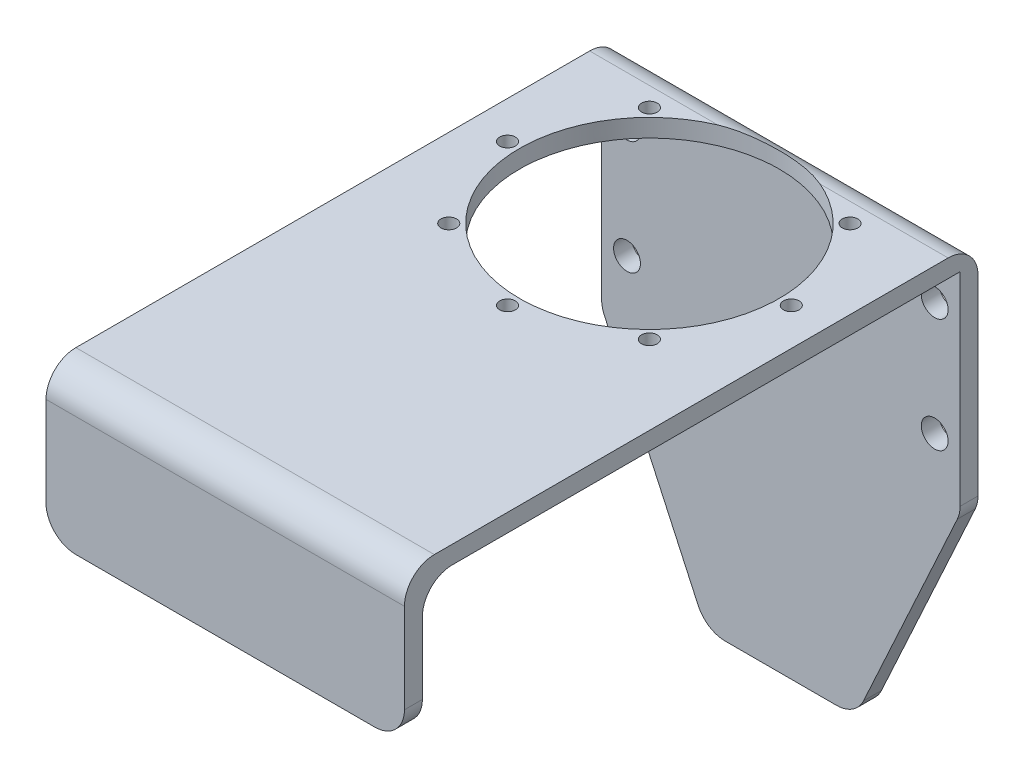
SolidWorks part; units mm, degrees
ref_plane "Alzado" through (0, 0, 0) normal (0, 0, 1) x (1, 0, 0)
ref_plane "Planta" through (0, 0, 0) normal (0, 1, 0) x (1, 0, 0)
ref_plane "Vista lateral" through (0, 0, 0) normal (1, 0, 0) x (0, 0, -1)
sketch "Croquis1" plane through (0, 0, 0) normal (0, 0, 1) x (1, 0, 0)
  line L7 (-92.102, -168.3) -> (-57.102, -244.5)
  line L8 (-92.102, -92.1) -> (27.898, -92.1) construction
  line L9 (-92.102, -92.1) -> (-92.102, -244.5) construction
  line L10 (-92.102, -244.5) -> (27.898, -244.5) construction
  line L11 (27.898, -92.1) -> (27.898, -244.5) construction
  line L12 (27.898, -92.1) -> (27.898, -244.5) construction
  line L13 (-92.102, -92.1) -> (27.898, -92.1) construction
  line L14 (-92.102, -92.1) -> (27.898, -92.1)
  line L15 (-92.102, -92.1) -> (-92.102, -168.3)
  line L17 (27.898, -92.1) -> (27.898, -168.3)
  line L22 (-57.102, -244.5) -> (-7.102, -244.5)
  line L23 (-7.102, -244.5) -> (27.898, -168.3)
  line L24 (-32.102, -168.3) -> (-32.102, -92.1) construction
  line L25 (-92.102, -168.3) -> (27.898, -168.3) construction
  line L26 (-32.102, -130.2) -> (-92.102, -130.2) construction
  line L27 (-62.102, -130.2) -> (-62.102, -92.1) construction
  circle A0 centre (-83.602, -111.15) radius 4.5
  circle A1 centre (-83.602, -149.25) radius 4.5
  circle A2 centre (19.398, -149.25) radius 4.5
  circle A3 centre (19.398, -111.15) radius 4.5
  point P5 (-32.102, -244.5)
  point P16 (-32.102, -244.5)
  point P21 (27.898, -168.3)
  point P24 (-62.102, -111.15)
  point P32 (-88.102, -111.15)
  dimension "D3" = 9
  dimension "D1" = 120
  dimension "D2" = 50
  dimension "D4" = 4
extrude "Saliente-Extruir1" add sketch "Croquis1" along normal blind 6
sketch "Croquis2" plane through (0, 0, 6) normal (0, 0, 1) x (1, 0, 0)
  line L0 (27.898, -168.3) -> (27.898, -92.1) construction
  line L6 (-92.102, -98.1) -> (27.898, -98.1)
  line L7 (-92.102, -98.1) -> (-92.102, -92.1)
  line L8 (-92.102, -92.1) -> (27.898, -92.1)
  line L9 (27.898, -98.1) -> (27.898, -92.1)
  dimension "D1" = 6
extrude "Saliente-Extruir2" add sketch "Croquis2" along normal up to surface (186 mm away)
sketch "Croquis3" plane through (0, 0, 192) normal (0, 0, 1) x (1, 0, 0)
  line L5 (-92.102, -98.1) -> (27.898, -98.1)
  line L6 (-92.102, -98.1) -> (-92.102, -142.1)
  line L7 (-92.102, -142.1) -> (27.898, -142.1)
  line L16 (27.898, -98.1) -> (27.898, -142.1)
  line L17 (27.898, -92.1) -> (-92.102, -92.1) construction
  line L18 (27.898, -168.3) -> (27.898, -98.1) construction
  dimension "50" = 50
extrude "Saliente-Extruir3" add sketch "Croquis3" against normal blind 6
fillet "Redondeo1" radius 10 9 edges at (-32.102, -98.1, 186) (-32.102, -92.1, 0) (-32.102, -92.1, 192) (-92.102, -142.1, 189) (27.898, -142.1, 189) (-92.102, -168.3, 3) (27.898, -168.3, 3) (-7.102, -244.5, 3) (-57.102, -244.5, 3)
sketch "Croquis4" plane through (0, -98.1, 0) normal (0, -1, 0) x (1, 0, 0)
  circle A2 centre (-65.6896, 16.4124) radius 2.621
  circle A3 centre (1.4855, 83.5876) radius 2.621
  circle A4 centre (1.4855, 83.5876) radius 2.621
  circle A5 centre (-65.6896, 16.4124) radius 2.621
  circle A6 centre (15.398, 50) radius 2.621
  circle A7 centre (15.398, 50) radius 2.621
  circle A9 centre (1.4855, 16.4124) radius 2.621
  circle A10 centre (1.4855, 16.4124) radius 2.621
  circle A12 centre (-65.6896, 83.5876) radius 2.621
  circle A13 centre (-65.6896, 83.5876) radius 2.621
  circle A15 centre (-79.602, 50) radius 2.621
  circle A16 centre (-32.102, 97.5) radius 2.621
  circle A17 centre (-32.102, 97.5) radius 2.621
  circle A18 centre (-79.602, 50) radius 2.621
  spline S0 degree 3 poles (-36.0819, 6.6207) (-32.1019, 6.4397) (-28.122, 6.6207) (-24.0966, 7.1778) (-20.0626, 8.1272) (-16.0093, 9.5102) (-12.0574, 11.3088) (-8.2311, 13.545) (-4.6252, 16.1753) (-1.2886, 19.1868) (1.7228, 22.5233) (4.3531, 26.1294) (6.5893, 29.9556) (8.3879, 33.9076) (9.7708, 37.9607) (10.7202, 41.9949) (11.2773, 46.0201) (11.4583, 50.0002) (11.2773, 53.98) (10.7201, 58.0055) (9.7707, 62.0395) (8.3878, 66.0927) (6.5892, 70.0446) (4.353, 73.8709) (1.7226, 77.4768) (-1.2888, 80.8135) (-4.6253, 83.8248) (-8.2314, 86.4552) (-12.0576, 88.6913) (-16.0096, 90.4899) (-20.0627, 91.8728) (-24.0969, 92.8222) (-28.1222, 93.3793) (-32.1022, 93.5603) (-36.0821, 93.3793) (-40.1075, 92.8222) (-44.1415, 91.8727) (-48.1948, 90.4898) (-52.1466, 88.6912) (-55.973, 86.455) (-59.5789, 83.8247) (-62.9155, 80.8132) (-65.9268, 77.4767) (-68.5572, 73.8706) (-70.7934, 70.0444) (-72.592, 66.0924) (-73.9748, 62.0393) (-74.9243, 58.0051) (-75.4813, 53.9799) (-75.6624, 49.9998) (-75.4813, 46.02) (-74.9242, 41.9945) (-73.9748, 37.9605) (-72.5918, 33.9073) (-70.7933, 29.9554) (-68.557, 26.1291) (-65.9267, 22.5232) (-62.9153, 19.1865) (-59.5787, 16.1752) (-55.9727, 13.5448) (-52.1465, 11.3087) (-48.1944, 9.5101) (-44.1414, 8.1272) (-40.1072, 7.1778) (-36.0819, 6.6207) (-32.1019, 6.4397) (-28.122, 6.6207) knots -0.04456 -0.029124 -0.014562 0 0.014563 0.029124 0.044561 0.059997 0.076078 0.092156 0.108579 0.125 0.141423 0.157844 0.173924 0.190003 0.20544 0.220876 0.235439 0.25 0.264563 0.279124 0.294561 0.309997 0.326078 0.342156 0.358579 0.375 0.391423 0.407844 0.423924 0.440003 0.45544 0.470876 0.485439 0.5 0.514563 0.529124 0.544561 0.559997 0.576078 0.592156 0.608579 0.625 0.641423 0.657844 0.673924 0.690003 0.70544 0.720876 0.735439 0.75 0.764563 0.779124 0.794561 0.809997 0.826078 0.842156 0.858579 0.875 0.891423 0.907844 0.923924 0.940003 0.95544 0.970876 0.985438 1 1.014563 1.029124 1.044561 only from (-32.102, 6.5) to (-32.102, 6.5) construction
  spline S1 degree 3 poles (-36.0819, 6.6207) (-32.1019, 6.4397) (-28.122, 6.6207) (-24.0966, 7.1778) (-20.0626, 8.1272) (-16.0093, 9.5102) (-12.0574, 11.3088) (-8.2311, 13.545) (-4.6252, 16.1753) (-1.2886, 19.1868) (1.7228, 22.5233) (4.3531, 26.1294) (6.5893, 29.9556) (8.3879, 33.9076) (9.7708, 37.9607) (10.7202, 41.9949) (11.2773, 46.0201) (11.4583, 50.0002) (11.2773, 53.98) (10.7201, 58.0055) (9.7707, 62.0395) (8.3878, 66.0927) (6.5892, 70.0446) (4.353, 73.8709) (1.7226, 77.4768) (-1.2888, 80.8135) (-4.6253, 83.8248) (-8.2314, 86.4552) (-12.0576, 88.6913) (-16.0096, 90.4899) (-20.0627, 91.8728) (-24.0969, 92.8222) (-28.1222, 93.3793) (-32.1022, 93.5603) (-36.0821, 93.3793) (-40.1075, 92.8222) (-44.1415, 91.8727) (-48.1948, 90.4898) (-52.1466, 88.6912) (-55.973, 86.455) (-59.5789, 83.8247) (-62.9155, 80.8132) (-65.9268, 77.4767) (-68.5572, 73.8706) (-70.7934, 70.0444) (-72.592, 66.0924) (-73.9748, 62.0393) (-74.9243, 58.0051) (-75.4813, 53.9799) (-75.6624, 49.9998) (-75.4813, 46.02) (-74.9242, 41.9945) (-73.9748, 37.9605) (-72.5918, 33.9073) (-70.7933, 29.9554) (-68.557, 26.1291) (-65.9267, 22.5232) (-62.9153, 19.1865) (-59.5787, 16.1752) (-55.9727, 13.5448) (-52.1465, 11.3087) (-48.1944, 9.5101) (-44.1414, 8.1272) (-40.1072, 7.1778) (-36.0819, 6.6207) (-32.1019, 6.4397) (-28.122, 6.6207) knots -0.04456 -0.029124 -0.014562 0 0.014563 0.029124 0.044561 0.059997 0.076078 0.092156 0.108579 0.125 0.141423 0.157844 0.173924 0.190003 0.20544 0.220876 0.235439 0.25 0.264563 0.279124 0.294561 0.309997 0.326078 0.342156 0.358579 0.375 0.391423 0.407844 0.423924 0.440003 0.45544 0.470876 0.485439 0.5 0.514563 0.529124 0.544561 0.559997 0.576078 0.592156 0.608579 0.625 0.641423 0.657844 0.673924 0.690003 0.70544 0.720876 0.735439 0.75 0.764563 0.779124 0.794561 0.809997 0.826078 0.842156 0.858579 0.875 0.891423 0.907844 0.923924 0.940003 0.95544 0.970876 0.985438 1 1.014563 1.029124 1.044561 only from (-32.102, 6.5) to (-32.102, 6.5)
  dimension "D1" = 1
  dimension "D2" = 1
  dimension "D3" = 1
  dimension "D4" = 1
  dimension "D5" = 1
  dimension "D6" = 1
  dimension "D7" = 1
extrude "Cortar-Extruir1" cut sketch "Croquis4" against normal through all
